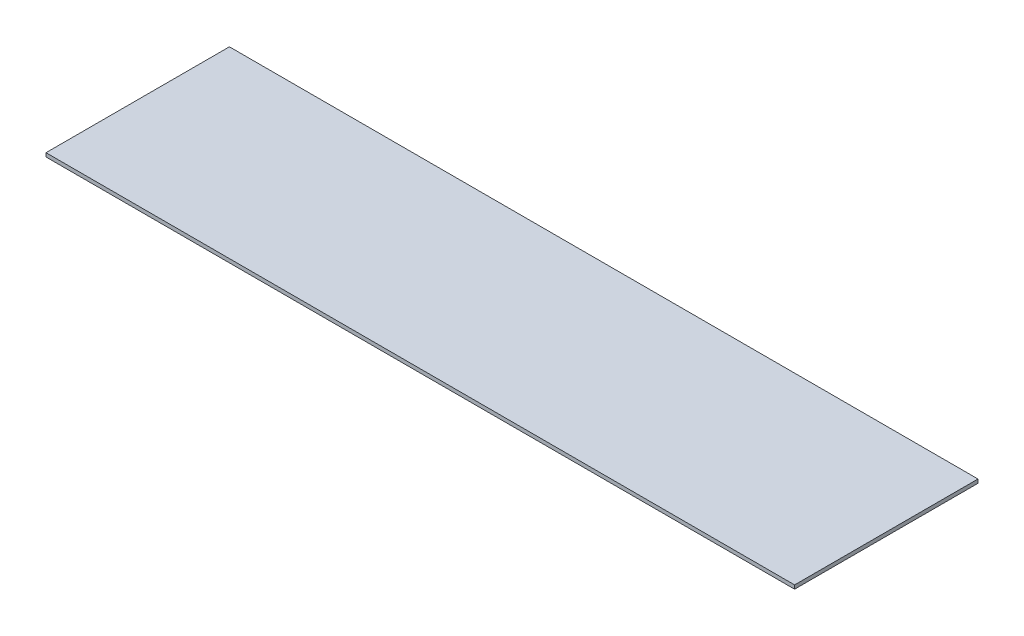
SolidWorks part; units mm, degrees
ref_plane "Ebene vorne" through (0, 0, 0) normal (0, 0, 1) x (1, 0, 0)
ref_plane "Ebene oben" through (0, 0, 0) normal (0, 1, 0) x (1, 0, 0)
ref_plane "Ebene rechts" through (0, 0, 0) normal (1, 0, 0) x (0, 0, -1)
sketch "Sketch1" plane through (0, 0, 0) normal (1, 0, 0) x (0, 0, -1)
  line L0 (0, 0) -> (0, 2)
  line L1 (0, 0) -> (98, 0)
  line L2 (98, 0) -> (98, 2)
  line L5 (0, 2) -> (98, 2)
  point P1 (99.7878, 2)
  dimension "D4" = 2
  dimension "D5" = 98
extrude "Boss-Extrude1" add sketch "Sketch1" along normal blind 400
